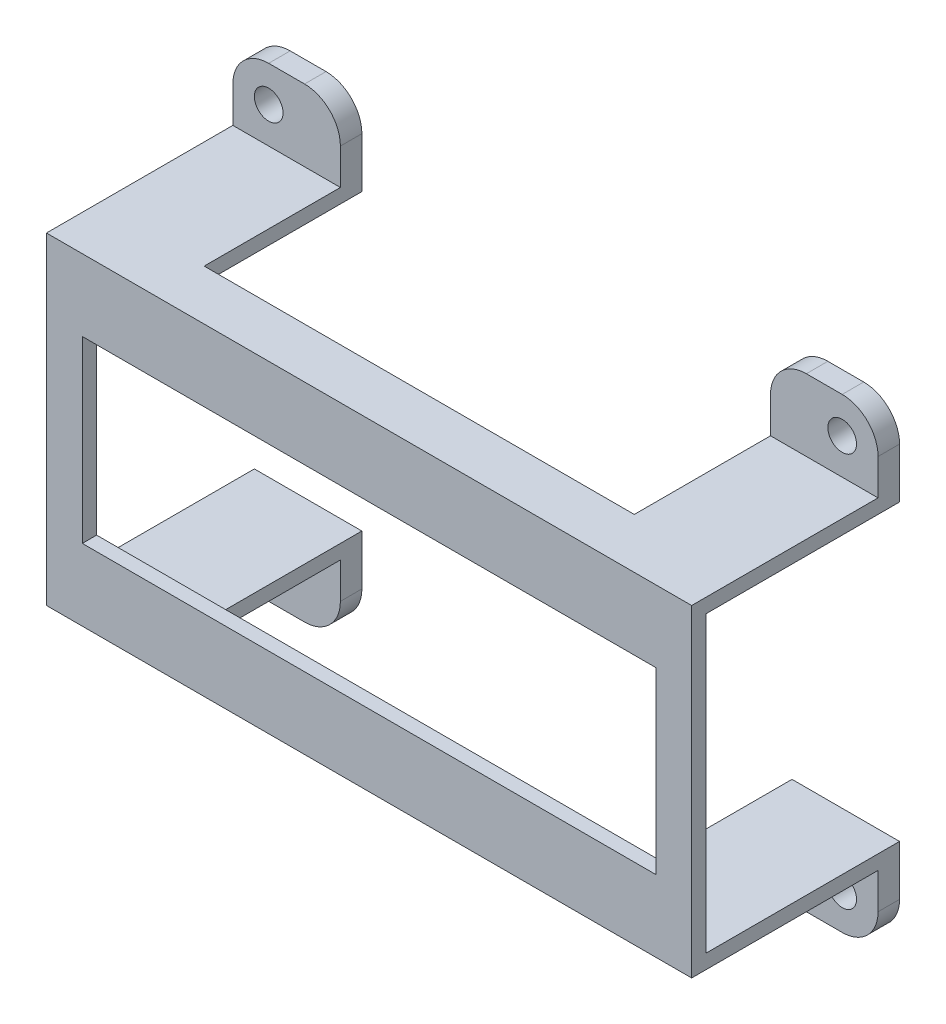
SolidWorks part; units mm, degrees
ref_plane "Front Plane" through (0, 0, 0) normal (0, 0, 1) x (1, 0, 0)
ref_plane "Top Plane" through (0, 0, 0) normal (0, 1, 0) x (1, 0, 0)
ref_plane "Right Plane" through (0, 0, 0) normal (1, 0, 0) x (0, 0, -1)
sketch "Sketch1" plane through (0, 0, 0) normal (0, 0, 1) x (1, 0, 0)
  line L1 (-45, -32.5) -> (45, -32.5)
  line L2 (-45, -32.5) -> (-45, 32.5)
  line L3 (-45, 32.5) -> (45, 32.5)
  line L4 (45, -32.5) -> (45, 32.5)
  line L5 (-45, -32.5) -> (45, 32.5) construction
  line L6 (-45, 32.5) -> (45, -32.5) construction
  point P0 (0, 0)
  dimension "D1" = 90
  dimension "D2" = 65
extrude "Boss-Extrude1" add sketch "Sketch1" along normal blind 3
fillet "Fillet4" radius 5 1 edges at (-45, -32.5, 1.5)
fillet "Fillet5" radius 5 1 edges at (45, -32.5, 1.5)
fillet "Fillet6" radius 5 1 edges at (45, 32.5, 1.5)
fillet "Fillet7" radius 5 1 edges at (-45, 32.5, 1.5)
sketch "Sketch4" plane through (0, 0, 3) normal (0, 0, 1) x (1, 0, 0)
  line L1 (-45, 22.5) -> (45, 22.5)
  line L2 (-45, 22.5) -> (-45, -22.5)
  line L3 (-45, -22.5) -> (45, -22.5)
  line L4 (45, 22.5) -> (45, -22.5)
  line L6 (-45, 32.5) -> (45, 32.5) construction
  line L7 (45, -27.5) -> (45, 27.5) construction
  dimension "D1" = 45
  dimension "D2" = 10
  dimension "D3" = 90
  dimension "D4" = 0
extrude "Boss-Extrude2" add sketch "Sketch4" along normal blind 26
sketch "Sketch5" plane through (0, 0, 29) normal (0, 0, 1) x (1, 0, 0)
  line L0 (45, -22.5) -> (45, 22.5) construction
  line L1 (-40, 12.5) -> (40, 12.5)
  line L2 (-40, 12.5) -> (-40, -12.5)
  line L3 (-40, -12.5) -> (40, -12.5)
  line L4 (40, 12.5) -> (40, -12.5)
  line L5 (45, 22.5) -> (-45, 22.5) construction
  line L6 (-45, -22.5) -> (45, -22.5) construction
  line L7 (-45, 22.5) -> (-45, -22.5) construction
  dimension "D1" = 5
  dimension "D2" = 10
  dimension "D3" = 10
  dimension "D4" = 5
sketch "Sketch6" plane through (0, 0, 0) normal (0, 0, -1) x (-1, 0, 0)
  line L1 (-45, 20.5) -> (45, 20.5)
  line L2 (-45, 20.5) -> (-45, -20.5)
  line L3 (-45, -20.5) -> (45, -20.5)
  line L4 (45, 20.5) -> (45, -20.5)
  line L6 (-45, -32.5) -> (-45, 32.5) construction
  line L8 (45, 32.5) -> (-45, 32.5) construction
  dimension "D1" = 41
  dimension "D2" = 90
  dimension "D3" = 0
  dimension "D4" = 12
extrude "Cut-Extrude2" cut sketch "Sketch6" against normal blind 27
extrude "Cut-Extrude3" cut sketch "Sketch5" against normal blind 3
sketch "Sketch7" plane through (0, 0, 3) normal (0, 0, 1) x (1, 0, 0)
  line L0 (-45, -22.5) -> (-45, -27.5) construction
  line L3 (45, -27.5) -> (45, -22.5) construction
  line L4 (-40, -32.5) -> (40, -32.5) construction
  circle A0 centre (40, -27.5) radius 2
  circle A1 centre (-40, -27.5) radius 2
  dimension "D1" = 4
  dimension "D2" = 4
  dimension "D5" = 5
  dimension "D3" = 80
  dimension "D4" = 5
  dimension "D6" = 5
extrude "Cut-Extrude4" cut sketch "Sketch7" against normal blind 3
sketch "Sketch8" plane through (0, 0, 3) normal (0, 0, 1) x (1, 0, 0)
  line L1 (45, 22.5) -> (45, 27.5) construction
  line L4 (40, 32.5) -> (-40, 32.5) construction
  circle A0 centre (-40, 27.5) radius 2
  circle A1 centre (40, 27.5) radius 2
  dimension "D1" = 80
  dimension "D5" = 4
  dimension "D6" = 4
  dimension "D2" = 5
  dimension "D3" = 5
  dimension "D4" = 5
extrude "Cut-Extrude5" cut sketch "Sketch8" against normal blind 3
sketch "Sketch10" plane through (0, 20.5, 0) normal (0, -1, 0) x (1, 0, 0)
  line L0 (-45, 0) -> (45, 0) construction
  line L1 (-30, 0) -> (30, 0)
  line L2 (-30, 0) -> (-30, 22)
  line L3 (-30, 22) -> (30, 22)
  line L4 (30, 0) -> (30, 22)
  line L5 (45, 27) -> (45, 0) construction
  line L6 (-45, 27) -> (45, 27) construction
  dimension "D1" = 15
  dimension "D2" = 60
  dimension "D3" = 5
extrude "Cut-Extrude7" cut sketch "Sketch10" against normal blind 12
fillet "Fillet9" radius 5 1 edges at (-30, 32.5, 1.5)
fillet "Fillet10" radius 5 1 edges at (30, 32.5, 1.5)
sketch "Sketch11" plane through (0, -20.5, 0) normal (0, 1, 0) x (1, 0, 0)
  line L0 (45, 0) -> (-45, 0) construction
  line L1 (30, 0) -> (-30, 0)
  line L2 (30, 0) -> (30, -22)
  line L3 (30, -22) -> (-30, -22)
  line L4 (-30, 0) -> (-30, -22)
  line L5 (45, -27) -> (45, 0) construction
  line L6 (45, -27) -> (-45, -27) construction
  dimension "D1" = 15
  dimension "D2" = 60
  dimension "D3" = 5
extrude "Cut-Extrude8" cut sketch "Sketch11" against normal blind 12
fillet "Fillet11" radius 5 1 edges at (30, -32.5, 1.5)
fillet "Fillet12" radius 5 1 edges at (-30, -32.5, 1.5)
